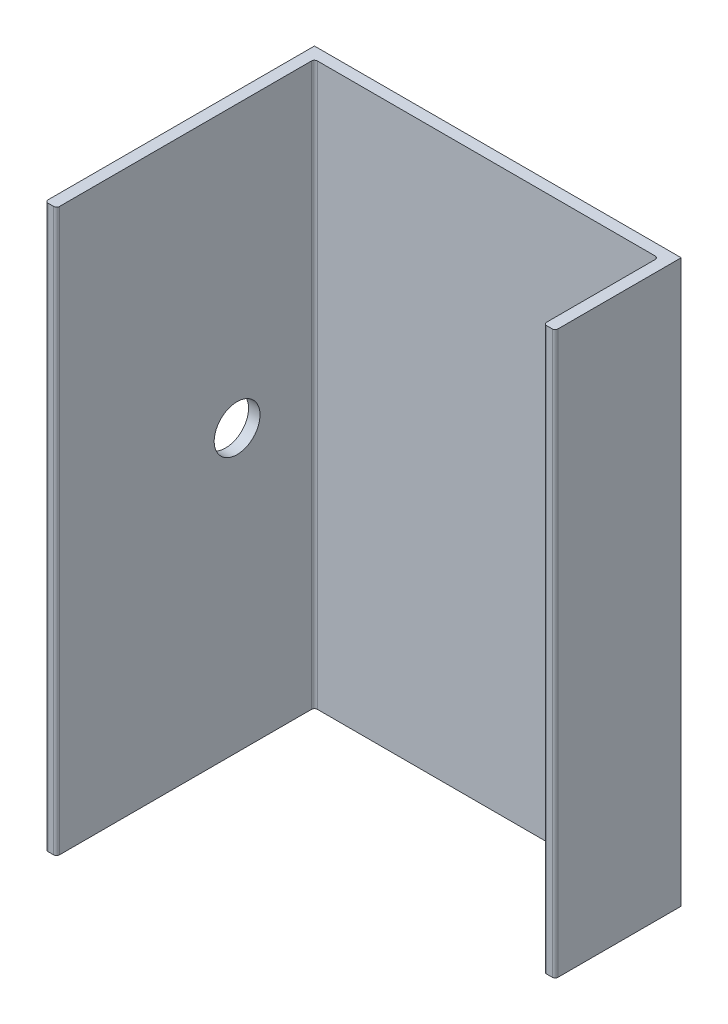
SolidWorks part; units mm, degrees
ref_plane "Piano frontale" through (0, 0, 0) normal (0, 0, 1) x (1, 0, 0)
ref_plane "Piano superiore" through (0, 0, 0) normal (0, 1, 0) x (1, 0, 0)
ref_plane "Piano destro" through (0, 0, 0) normal (1, 0, 0) x (0, 0, -1)
sketch "Schizzo1" plane through (0, 0, 0) normal (0, 0, 1) x (1, 0, 0)
  line L1 (-32, 49) -> (32, 49)
  line L2 (-32, 49) -> (-32, -49)
  line L3 (-32, -49) -> (32, -49)
  line L4 (32, 49) -> (32, -49)
  line L5 (-32, 49) -> (-30, 45.9375) construction
  line L6 (-32, -49) -> (0, 0) construction
  line L15 (0, 0) -> (32, -49) construction
  line L16 (30, 45.9375) -> (32, 49) construction
  point P0 (0, 0)
  dimension "D1" = 64
  dimension "D2" = 98
extrude "Estrusione-Estrusione1" add sketch "Schizzo1" against normal blind 2
sketch "Schizzo4" plane through (0, 0, 0) normal (0, 0, 1) x (1, 0, 0)
  line L0 (-32, -49) -> (32, -49) construction
  line L1 (-32, 49) -> (-30, 49)
  line L2 (-32, 49) -> (-32, -49)
  line L3 (-32, -49) -> (-30, -49)
  line L4 (-30, 49) -> (-30, -49)
  dimension "D1" = 2
extrude "Estrusione-Estrusione2" add sketch "Schizzo4" along normal blind 45
sketch "Schizzo5" plane through (0, 0, 0) normal (0, 0, 1) x (1, 0, 0)
  line L0 (-30, -49) -> (32, -49) construction
  line L1 (32, 49) -> (30, 49)
  line L2 (32, 49) -> (32, -49)
  line L3 (32, -49) -> (30, -49)
  line L4 (30, 49) -> (30, -49)
  dimension "D1" = 2
extrude "Estrusione-Estrusione3" add sketch "Schizzo5" along normal blind 20
fillet "Raccordo1" radius 0.5 6 edges at (32, 0, 20) (30, 0, 20) (30, 0, 0) (-30, 0, 0) (-32, 0, 45) (-30, 0, 45)
sketch "Schizzo6" plane through (-32, 0, 0) normal (-1, 0, 0) x (0, 0, 1)
  line L0 (44.5, 0) -> (-2, 0) construction
  line L1 (44.5, -49) -> (44.5, 49) construction
  line L2 (-2, 49) -> (-2, -49) construction
  circle A0 centre (13.5, 0) radius 4
  dimension "D1" = 8
  dimension "D2" = 15.5
extrude "Taglio-Estrusione1" cut sketch "Schizzo6" against normal blind 10
